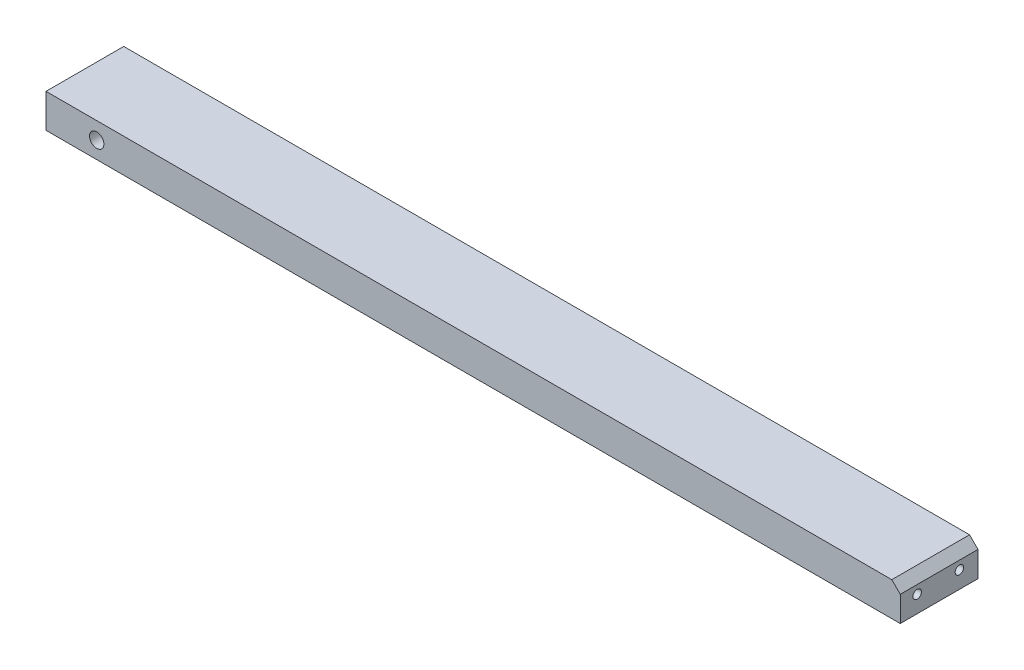
SolidWorks part; units mm, degrees
material "3.3535 (Al Mg3)"
ref_plane "Vorne" through (0, 0, 0) normal (0, 0, 1) x (1, 0, 0)
ref_plane "Oben" through (0, 0, 0) normal (0, 1, 0) x (1, 0, 0)
ref_plane "Rechts" through (0, 0, 0) normal (1, 0, 0) x (0, 0, -1)
sketch "Skizze1" plane through (0, 0, 0) normal (0, 0, 1) x (1, 0, 0)
  line L0 (-252.75, 10) -> (252.75, -10) construction
  line L1 (-252.75, 10) -> (252.75, 10)
  line L2 (-252.75, 10) -> (-252.75, -10)
  line L3 (-252.75, -10) -> (252.75, -10)
  line L4 (252.75, 10) -> (252.75, -10)
  dimension "D1" = 20
  dimension "D2" = 505.5
extrude "Linear austragen1" add sketch "Skizze1" along normal blind 46
hole_wizard "M10 Gewindebohrung1" positions "Skizze5" profile "Skizze4" tap size "M10" standard "Gabler-Normteile"
sketch "Skizze5" plane through (-252.75, 0, 0) normal (-1, 0, 0) x (0, 0, 1)
  line L0 (46, 10) -> (46, -10) construction
  point P0 (11, 0)
  dimension "D1" = 35
sketch "Skizze4" plane through (-252.75, 0, 11) normal (0, 1, 0) x (0, 0, 1)
  line L0 (0, 0) -> (0, 30.0537)
  line L1 (0, 30.0537) -> (4.25, 27.5)
  line L2 (4.25, 27.5) -> (4.25, 0.775)
  line L3 (4.25, 0.775) -> (5.025, 0)
  line L5 (5.025, 0) -> (0, 0)
  line L6 (-4.25, 0.775) -> (-5.025, 0) construction
  line L10 (0, 30.0537) -> (-4.25, 27.5) construction
  line L11 (0, -6.35) -> (0, 107.95) construction
  dimension "Bohrerdurchmesser" = 8.5
  dimension "Bohrungstiefe" = 27.5
  dimension "Senkdurchmesser (Oben)" = 10.05
  dimension "Senkwinkel (Oben)" = 90
  dimension "Spitzenwinkel" = 118
cosmetic thread "Bohrungsgewinde4" parameters "D1"=20, "D2"=10
hole_wizard "Ø8.0 (8) Durchmesser Bohrung1" positions "Skizze13" profile "Skizze12" hole size "Ø8.0" standard "Gabler-Normteile"
sketch "Skizze13" plane through (-252.75, 0, 0) normal (-1, 0, 0) x (0, 0, 1)
  point P0 (36, 0)
  dimension "D1" = 25
sketch "Skizze12" plane through (-252.75, 0, 36) normal (0, 1, 0) x (0, 0, 1)
  line L0 (0, 0) -> (0, 12.4034)
  line L1 (0, 12.4034) -> (4, 10)
  line L2 (4, 10) -> (4, 0)
  line L5 (4, 0) -> (0, 0)
  line L10 (0, 12.4034) -> (-4, 10) construction
  line L11 (0, -6.35) -> (0, 107.95) construction
  dimension "Bohrerdurchmesser" = 8
  dimension "Bohrungstiefe" = 10
  dimension "Spitzenwinkel" = 118
hole_wizard "M10 Gewindebohrung2" positions "Skizze15" profile "Skizze14" tap size "M10" standard "Gabler-Normteile"
sketch "Skizze15" plane through (0, 0, 46) normal (0, 0, 1) x (1, 0, 0)
  line L0 (-252.75, 10) -> (-252.75, -10) construction
  point P0 (-222.75, 0)
  dimension "D1" = 30
sketch "Skizze14" plane through (-222.75, 0, 46) normal (1, 0, 0) x (0, -1, 0)
  line L0 (0, 0) -> (0, 30.0537)
  line L1 (0, 30.0537) -> (4.25, 27.5)
  line L2 (4.25, 27.5) -> (4.25, 0)
  line L5 (4.25, 0) -> (0, 0)
  line L10 (0, 30.0537) -> (-4.25, 27.5) construction
  line L11 (0, -6.35) -> (0, 107.95) construction
  dimension "Bohrerdurchmesser" = 8.5
  dimension "Bohrungstiefe" = 27.5
  dimension "Spitzenwinkel" = 118
cosmetic thread "Bohrungsgewinde9" parameters "D1"=20, "D2"=10
hole_wizard "M6 Gewindebohrung1" positions "Skizze17" profile "Skizze16" tap size "M6" standard "Gabler-Normteile"
sketch "Skizze17" plane through (252.75, -240.7719, -2.6047) normal (-1, 0, 0) x (0, 1, 0)
  line L0 (250.7719, -48.6047) -> (250.7719, -2.6047) construction
  point P0 (240.7719, -13.6047)
  point P2 (240.7719, -38.6047)
  dimension "D1" = 10
cosmetic thread "Bohrungsgewinde10" parameters "D1"=12, "D2"=6
sketch "Skizze16" plane through (252.75, 0, 11) normal (0, 1, 0) x (0, 0, -1)
  line L0 (0, 0) -> (0, 18.5022)
  line L1 (0, 18.5022) -> (2.5, 17)
  line L2 (2.5, 17) -> (2.5, 0)
  line L5 (2.5, 0) -> (0, 0)
  line L10 (0, 18.5022) -> (-2.5, 17) construction
  line L11 (0, -6.35) -> (0, 107.95) construction
  dimension "Bohrerdurchmesser" = 5
  dimension "Bohrungstiefe" = 17
  dimension "Spitzenwinkel" = 118
cosmetic thread "Bohrungsgewinde12" parameters "D1"=12, "D2"=6
chamfer "Fase1" distance 5 angle 45 1 edges at (252.75, 10, 23)
